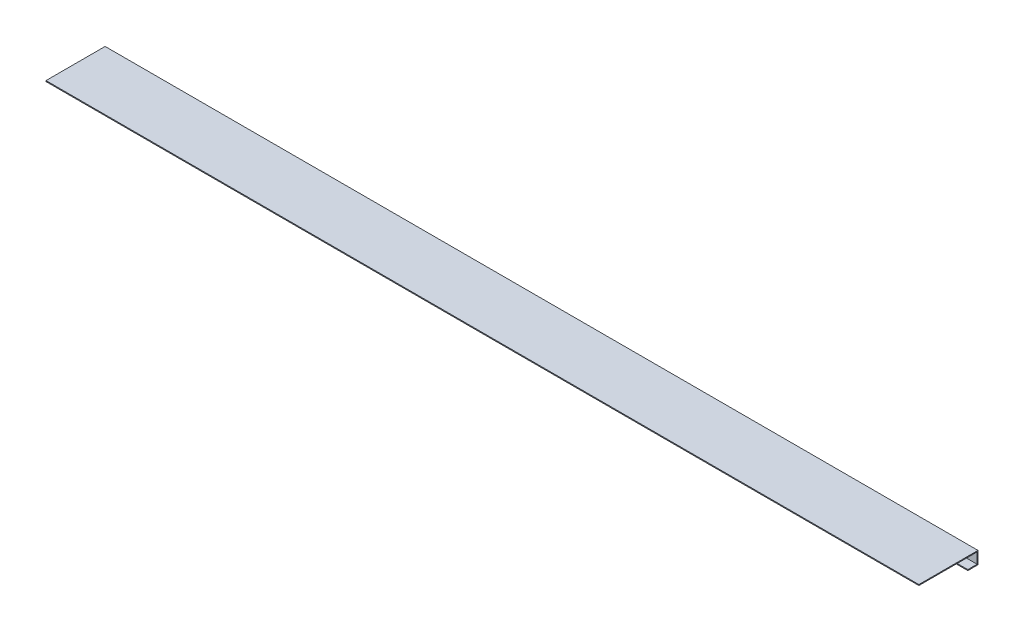
SolidWorks part; units mm, degrees
ref_plane "Front Plane" through (0, 0, 0) normal (0, 0, 1) x (1, 0, 0)
ref_plane "Top Plane" through (0, 0, 0) normal (0, 1, 0) x (1, 0, 0)
ref_plane "Right Plane" through (0, 0, 0) normal (1, 0, 0) x (0, 0, -1)
sketch "Sketch1" plane through (0, 0, 0) normal (1, 0, 0) x (0, 0, -1)
  line L0 (0, 0) -> (128, 0)
  line L1 (128, 0) -> (128, -27)
  line L2 (128, -27) -> (106, -27)
  line L3 (0, -2) -> (126, -2)
  line L4 (126, -2) -> (126, -25)
  line L5 (126, -25) -> (106, -25)
  line L6 (0, 0) -> (0, -2)
  line L7 (106, -27) -> (106, -25)
  dimension "D1" = 2
  dimension "D2" = 128
  dimension "D3" = 27
  dimension "D4" = 22
extrude "Boss-Extrude1" add sketch "Sketch1" along normal blind 1890
equation "\"door_base_long7_R1_R_open_Single_height\"=1890.0"
equation "\"D1@Boss-Extrude1\"=\"door_base_long7_R1_R_open_Single_height\""
equation "\"CarBeamWidth\"=700.0"
equation "\"WheelWidth\"=650.0"
equation "\"Wheel_FrontBoxDistance\"=1390.0"
equation "\"MetalSheet_3mm_length\"=5030.0"
equation "\"MetalSheet_3mm_width\"=1923.0"
equation "\"MetalSheet_3mm_FloorCut_L_length\"=1764.0"
equation "\"MetalSheet_3mm_FloorCut_L_disdance\"=1665.0"
equation "\"MetalSheet_3mm_FloorCut_R_length\"=1764.0"
equation "\"MetalSheet_3mm_FloorCut_R_disdance\"=1665.0"
equation "\"indoorHeight\"=1940.0"
equation "\"haveDoor_R\"=1"
equation "\"side_door_bottom_R_3mm_length\"=1934.0"
equation "\"1Bar_Side_RF_3mm_length\"=1493.0"
equation "\"1Bar_Side_RB_3mm_length\"=1493.0"
equation "\"DoorSeparator_RF_3mm_withHinge_toFrontDistance\"=1673.0"
equation "\"DoorSeparator_RF_3mm_withHinge_exist\"=1"
equation "\"DoorSeparator_RB_3mm_withHinge_toFrontDistance\"=3427.0"
equation "\"DoorSeparator_RB_3mm_withHinge_exist\"=1"
equation "\"Door_R1_L_open_Single_toFrontDistance\"=2547.5"
equation "\"Door_R1_L_open_Single_exist\"=1"
equation "\"door_base_long7_R1_L_open_Single_height\"=1890.0"
equation "\"door_base_short7_R1_L_open_Single_height\"=1890.0"
equation "\"door_base_short7_R1_L_open_Single_width\"=864"
equation "\"Door_R1_R_open_Single_toFrontDistance\"=3422.0"
equation "\"Door_R1_R_open_Single_exist\"=1"
equation "\"door_base_short7_R1_R_open_Single_height\"=1890.0"
equation "\"door_base_short7_R1_R_open_Single_width\"=864"
equation "\"x\"=66.0"
equation "\"da\"=62.0"
equation "\"SquareTube_length\"=1923.0"
equation "\"channelSteel_length\"=5030.0"
equation "\"SquareTube_inFront_AvgDistance\"=285.0"
equation "\"SquareTube_inFront_TotalCount\"=5"
equation "\"SquareTube_inFront1_cutDepth50_R\"=0.5"
equation "\"SquareTube_inFront1_cutDepth50_L\"=0.5"
equation "\"SquareTube_inFront2_cutDepth50_R\"=0.5"
equation "\"SquareTube_inFront2_cutDepth50_L\"=0.5"
equation "\"SquareTube_inFront3_cutDepth50_R\"=0.5"
equation "\"SquareTube_inFront3_cutDepth50_L\"=0.5"
equation "\"SquareTube_inFront4_cutDepth50_R\"=0.5"
equation "\"SquareTube_inFront4_cutDepth50_L\"=0.5"
equation "\"SquareTube_inFront5_cutDepth50_R\"=50"
equation "\"SquareTube_inFront5_cutDepth50_L\"=50"
equation "\"SquareTube_inFront6_cutDepth50_R\"=50"
equation "\"SquareTube_inFront6_cutDepth50_L\"=50"
equation "\"SquareTube_inFront7_cutDepth50_R\"=50"
equation "\"SquareTube_inFront7_cutDepth50_L\"=50"
equation "\"SquareTube_inFront8_cutDepth50_R\"=50"
equation "\"SquareTube_inFront8_cutDepth50_L\"=50"
equation "\"SquareTube_inFront9_cutDepth50_R\"=50"
equation "\"SquareTube_inFront9_cutDepth50_L\"=50"
equation "\"SquareTube_inFront10_cutDepth50_R\"=50"
equation "\"SquareTube_inFront10_cutDepth50_L\"=50"
equation "\"SquareTube_inFront11_cutDepth50_R\"=50"
equation "\"SquareTube_inFront11_cutDepth50_L\"=50"
equation "\"SquareTube_inFront12_cutDepth50_R\"=50"
equation "\"SquareTube_inFront12_cutDepth50_L\"=50"
equation "\"SquareTube_inFront13_cutDepth50_R\"=50"
equation "\"SquareTube_inFront13_cutDepth50_L\"=50"
equation "\"SquareTube_inFront14_cutDepth50_R\"=50"
equation "\"SquareTube_inFront14_cutDepth50_L\"=50"
equation "\"SquareTube_inBack_AvgDistance\"=333.125"
equation "\"SquareTube_inBack_TotalCount\"=9"
equation "\"SquareTube_inBack1_cutDepth50_R\"=50"
equation "\"SquareTube_inBack1_cutDepth50_L\"=50"
equation "\"SquareTube_inBack2_cutDepth50_R\"=50"
equation "\"SquareTube_inBack2_cutDepth50_L\"=50"
equation "\"SquareTube_inBack3_cutDepth50_R\"=50"
equation "\"SquareTube_inBack3_cutDepth50_L\"=50"
equation "\"SquareTube_inBack4_cutDepth50_R\"=50"
equation "\"SquareTube_inBack4_cutDepth50_L\"=50"
equation "\"SquareTube_inBack5_cutDepth50_R\"=50"
equation "\"SquareTube_inBack5_cutDepth50_L\"=50"
equation "\"SquareTube_inBack6_cutDepth50_R\"=0.5"
equation "\"SquareTube_inBack6_cutDepth50_L\"=0.5"
equation "\"SquareTube_inBack7_cutDepth50_R\"=0.5"
equation "\"SquareTube_inBack7_cutDepth50_L\"=0.5"
equation "\"SquareTube_inBack8_cutDepth50_R\"=0.5"
equation "\"SquareTube_inBack8_cutDepth50_L\"=0.5"
